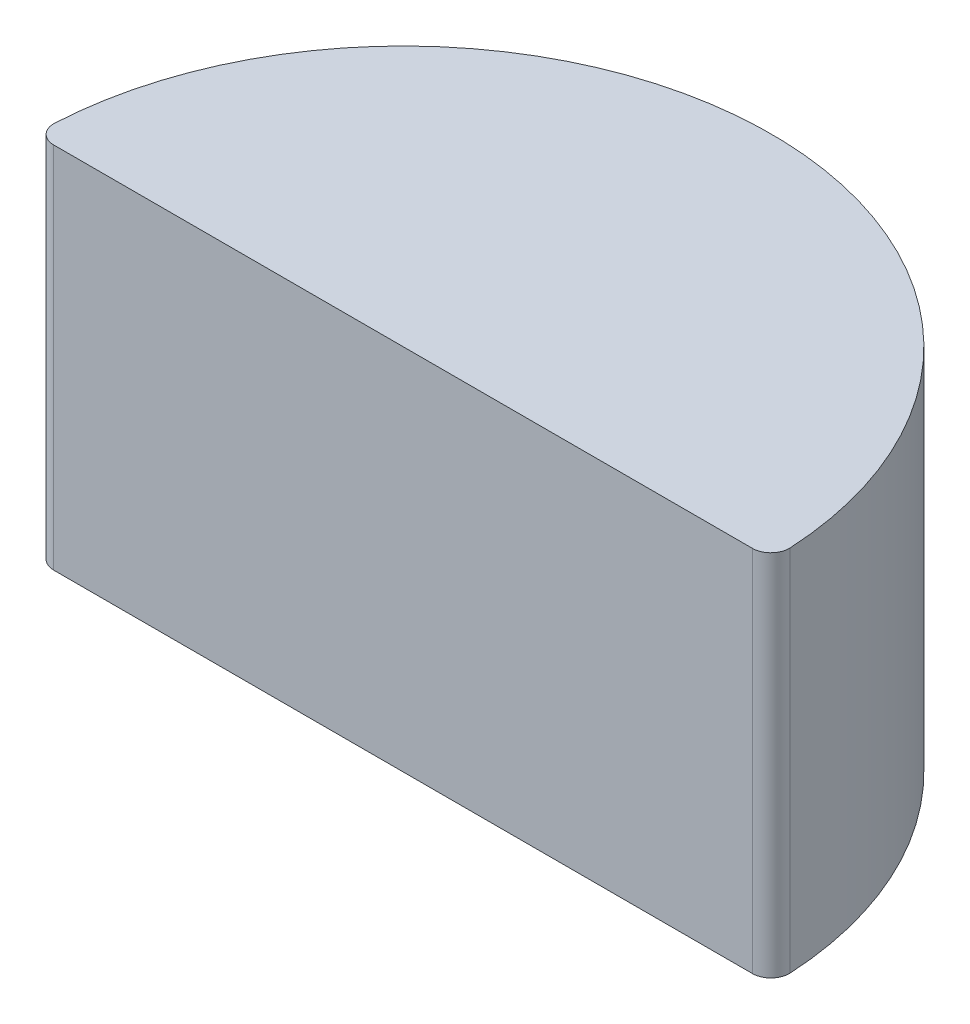
SolidWorks part; units mm, degrees
material "PVC 0.007 Plasticized"
ref_plane "Front Plane" through (0, 0, 0) normal (0, 0, 1) x (1, 0, 0)
ref_plane "Top Plane" through (0, 0, 0) normal (0, 1, 0) x (1, 0, 0)
ref_plane "Right Plane" through (0, 0, 0) normal (1, 0, 0) x (0, 0, -1)
sketch "Sketch1" plane through (0, 0, 0) normal (0, 1, 0) x (1, 0, 0)
  line L0 (0, 0) -> (40, 0)
  arc A0 (0, 0) -> (40, 0) centre (20, 0) cw
  dimension "D1" = 40
extrude "Boss-Extrude1" add sketch "Sketch1" along normal blind 20
fillet "Fillet1" radius 1 2 edges at (0, 10, 0) (40, 10, 0)
